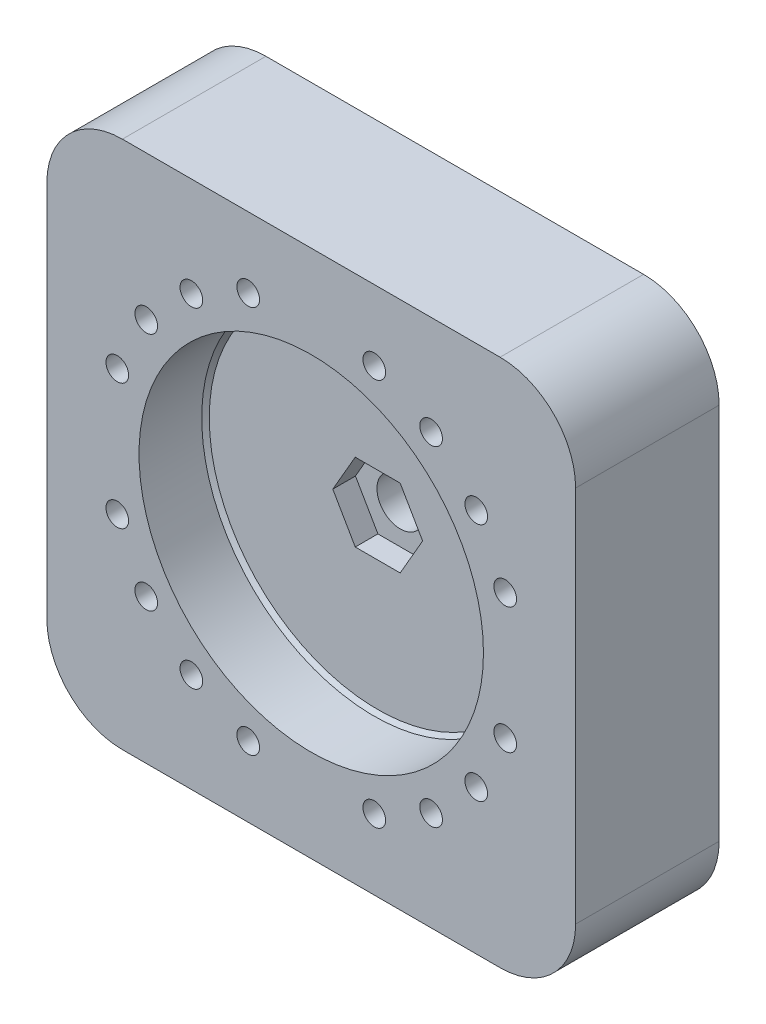
SolidWorks part; units mm, degrees
ref_plane "Спереди" through (0, 0, 0) normal (0, 0, 1) x (1, 0, 0)
ref_plane "Сверху" through (0, 0, 0) normal (0, 1, 0) x (1, 0, 0)
ref_plane "Справа" through (0, 0, 0) normal (1, 0, 0) x (0, 0, -1)
sketch "Эскиз1" plane through (0, 0, 0) normal (0, 0, 1) x (1, 0, 0)
  line L1 (-35, -35) -> (35, -35)
  line L2 (-35, -35) -> (-35, 35)
  line L3 (-35, 35) -> (35, 35)
  line L4 (35, -35) -> (35, 35)
  line L5 (-35, -35) -> (35, 35) construction
  line L6 (-35, 35) -> (35, -35) construction
  point P0 (0, 0)
  dimension "D1" = 70
extrude "Бобышка-Вытянуть1" add sketch "Эскиз1" along normal blind 19
sketch "Эскиз2" plane through (0, 0, 19) normal (0, 0, 1) x (1, 0, 0)
  circle A0 centre (0, 0) radius 22.8
  dimension "D1" = 45.6
extrude "Вырез-Вытянуть1" cut sketch "Эскиз2" against normal blind 8.8
sketch "Эскиз3" plane through (0, 0, 19) normal (0, 0, 1) x (1, 0, 0)
  line L0 (0, 0) -> (0, 20.26) construction
  line L1 (-8.3435, 25.6785) -> (0, 0) construction
  circle A0 centre (-8.3435, 25.6785) radius 1.5
  circle A1 centre (0, 27) radius 1.5 [skipped]
  circle A2 centre (8.3435, 25.6785) radius 1.5
  circle A3 centre (15.8702, 21.8435) radius 1.5
  circle A4 centre (21.8435, 15.8702) radius 1.5
  circle A5 centre (25.6785, 8.3435) radius 1.5
  circle A6 centre (27, 0) radius 1.5 [skipped]
  circle A7 centre (25.6785, -8.3435) radius 1.5
  circle A8 centre (21.8435, -15.8702) radius 1.5
  circle A9 centre (15.8702, -21.8435) radius 1.5
  circle A10 centre (8.3435, -25.6785) radius 1.5
  circle A11 centre (0, -27) radius 1.5 [skipped]
  circle A12 centre (-8.3435, -25.6785) radius 1.5
  circle A13 centre (-15.8702, -21.8435) radius 1.5
  circle A14 centre (-21.8435, -15.8702) radius 1.5
  circle A15 centre (-25.6785, -8.3435) radius 1.5
  circle A16 centre (-27, 0) radius 1.5 [skipped]
  circle A17 centre (-25.6785, 8.3435) radius 1.5
  circle A18 centre (-21.8435, 15.8702) radius 1.5
  circle A19 centre (-15.8702, 21.8435) radius 1.5
  point P46 (0, 0)
  dimension "D1" = 27
  dimension "D2" = 3
  dimension "D3" = 18
  dimension "D4" = 20
extrude "Вырез-Вытянуть2" cut sketch "Эскиз3" against normal up to surface (19 mm away) up to face at (0, 0, 0)
sketch "Эскиз5" plane through (0, 0, 0) normal (0, 0, -1) x (-1, 0, 0)
  circle A16 centre (-8.3435, 25.6785) radius 3.25
  circle A17 centre (0, 0) radius 27 construction
  circle A18 centre (0, 27) radius 3.25 [skipped]
  circle A19 centre (0, 0) radius 27 construction
  circle A20 centre (8.3435, 25.6785) radius 3.25
  circle A21 centre (0, 0) radius 27 construction
  circle A22 centre (15.8702, 21.8435) radius 3.25
  circle A23 centre (0, 0) radius 27 construction
  circle A24 centre (21.8435, 15.8702) radius 3.25
  circle A25 centre (0, 0) radius 27 construction
  circle A26 centre (25.6785, 8.3435) radius 3.25
  circle A27 centre (0, 0) radius 27 construction
  circle A28 centre (27, 0) radius 3.25 [skipped]
  circle A29 centre (0, 0) radius 27 construction
  circle A30 centre (25.6785, -8.3435) radius 3.25
  circle A31 centre (0, 0) radius 27 construction
  circle A32 centre (21.8435, -15.8702) radius 3.25
  circle A33 centre (0, 0) radius 27 construction
  circle A34 centre (15.8702, -21.8435) radius 3.25
  circle A35 centre (0, 0) radius 27 construction
  circle A36 centre (8.3435, -25.6785) radius 3.25
  circle A37 centre (0, 0) radius 27 construction
  circle A38 centre (0, -27) radius 3.25 [skipped]
  circle A39 centre (0, 0) radius 27 construction
  circle A40 centre (-8.3435, -25.6785) radius 3.25
  circle A41 centre (0, 0) radius 27 construction
  circle A42 centre (-15.8702, -21.8435) radius 3.25
  circle A43 centre (0, 0) radius 27 construction
  circle A44 centre (-21.8435, -15.8702) radius 3.25
  circle A45 centre (0, 0) radius 27 construction
  circle A46 centre (-25.6785, -8.3435) radius 3.25
  circle A47 centre (0, 0) radius 27 construction
  circle A48 centre (-27, 0) radius 3.25 [skipped]
  circle A49 centre (0, 0) radius 27 construction
  circle A50 centre (-25.6785, 8.3435) radius 3.25
  circle A51 centre (0, 0) radius 27 construction
  circle A52 centre (-21.8435, 15.8702) radius 3.25
  circle A53 centre (0, 0) radius 27 construction
  circle A54 centre (-15.8702, 21.8435) radius 3.25
  circle A55 centre (0, 0) radius 27 construction
  point P67 (0, 0)
  dimension "D1" = 6.5
  dimension "D2" = 20
extrude "Вырез-Вытянуть3" cut sketch "Эскиз5" against normal blind 2
sketch "Эскиз6" plane through (0, 0, 0) normal (0, 0, -1) x (-1, 0, 0)
  line L0 (-19, 0) -> (19, 0) construction
  line L1 (0, -19) -> (0, 19) construction
  circle A1 centre (0, -19) radius 3.1
  circle A3 centre (0, 19) radius 3.1
  circle A5 centre (-19, 0) radius 3.1
  circle A6 centre (19, 0) radius 3.1
  circle A7 centre (0, 19) radius 4 construction
  circle A8 centre (19, 0) radius 4 construction
  circle A9 centre (-19, 0) radius 4 construction
  circle A10 centre (0, -19) radius 4 construction
  circle A11 centre (0, 0) radius 3.1
  point P13 (0, 0)
  point P14 (0, 0)
  dimension "D1" = 6.2
  dimension "D2" = 38
  dimension "D3" = 8
extrude "Вырез-Вытянуть4" cut sketch "Эскиз6" against normal blind 7.5
chamfer "Фаска2" distance 0.5 angle 45 1 edges at (22.8, 0, 10.2)
sketch "Эскиз7" plane through (0, 0, 10.2) normal (0, 0, 1) x (1, 0, 0)
  line L1 (-2.9734, 5.15) -> (-5.9467, 0)
  line L2 (-5.9467, 0) -> (-2.9734, -5.15)
  line L3 (-2.9734, -5.15) -> (2.9734, -5.15)
  line L4 (2.9734, -5.15) -> (5.9467, 0)
  line L5 (5.9467, 0) -> (2.9734, 5.15)
  line L6 (2.9734, 5.15) -> (-2.9734, 5.15)
  circle A0 centre (0, 0) radius 5.15 construction
  dimension "D1" = 10.3
extrude "Вырез-Вытянуть5" cut sketch "Эскиз7" against normal blind 3
fillet "Скругление1" radius 10 4 edges at (35, 35, 9.5) (-35, 35, 9.5) (35, -35, 9.5) (-35, -35, 9.5)
